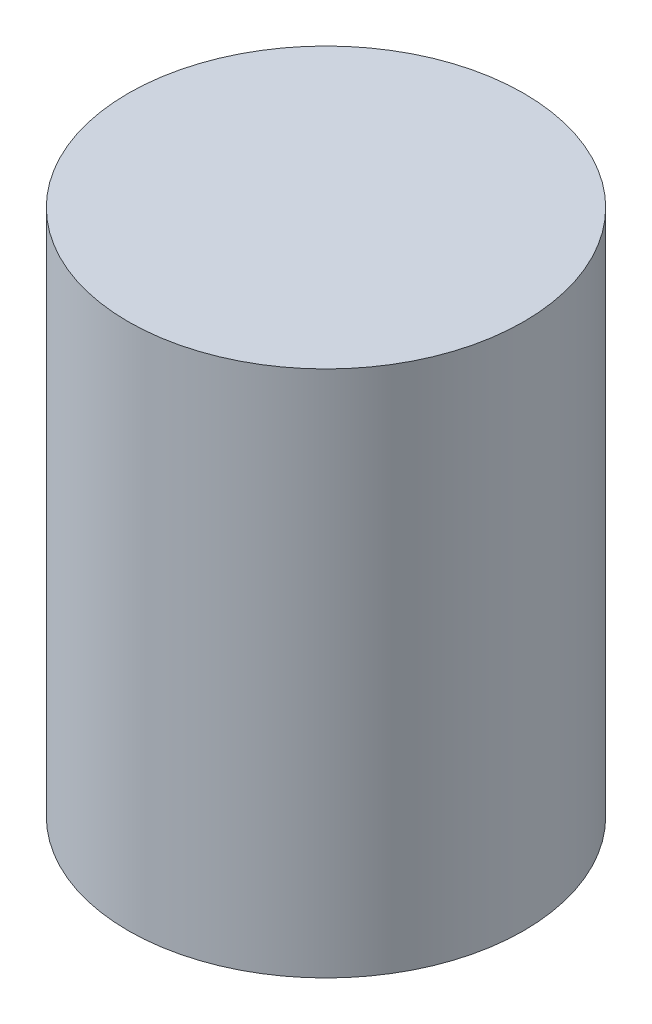
SolidWorks part; units mm, degrees
ref_plane "Front Plane" through (0, 0, 0) normal (0, 0, 1) x (1, 0, 0)
ref_plane "Top Plane" through (0, 0, 0) normal (0, 1, 0) x (1, 0, 0)
ref_plane "Right Plane" through (0, 0, 0) normal (1, 0, 0) x (0, 0, -1)
other "Configuration Table"
sketch "Sketch1" plane through (0, 0, 0) normal (0, 1, 0) x (1, 0, 0)
  circle A0 centre (0, 0) radius 15
extrude "KOLA1L_boyun_D30" add sketch "Sketch1" along normal blind 40 from offset 225 separate body
